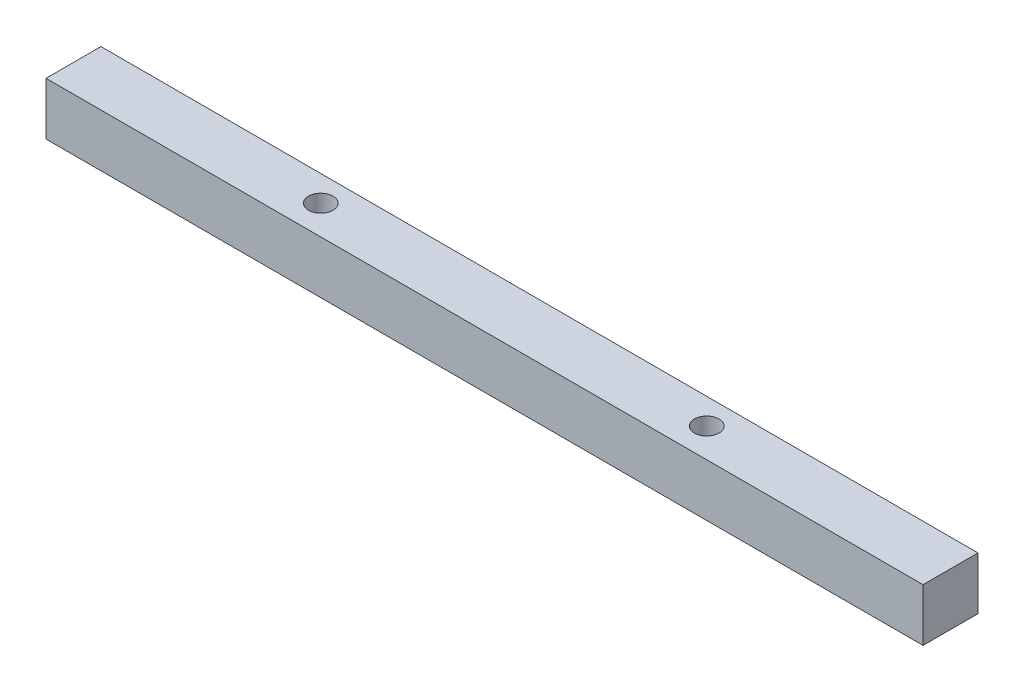
SolidWorks part; units mm, degrees
ref_plane "Front Plane" through (0, 0, 0) normal (0, 0, 1) x (1, 0, 0)
ref_plane "Top Plane" through (0, 0, 0) normal (0, 1, 0) x (1, 0, 0)
ref_plane "Right Plane" through (0, 0, 0) normal (1, 0, 0) x (0, 0, -1)
sketch "Sketch1" plane through (0, 0, 0) normal (1, 0, 0) x (0, 0, -1)
  line L1 (0, 0) -> (9.4, 0)
  line L2 (0, 0) -> (0, 9)
  line L3 (0, 9) -> (9.4, 9)
  line L4 (9.4, 0) -> (9.4, 9)
  dimension "D1" = 9.4
  dimension "D2" = 9
extrude "Boss-Extrude1" add sketch "Sketch1" along normal blind 150
sketch "Sketch2" plane through (0, 9, 0) normal (0, 1, 0) x (1, 0, 0)
  line L0 (75, 9.4) -> (75, 0) construction
  line L1 (150, 9.4) -> (0, 9.4) construction
  line L2 (150, 0) -> (0, 0) construction
  circle A0 centre (108, 4.9985) radius 2.1
  circle A1 centre (42, 4.9985) radius 2.1
  point P6 (75, 0)
  dimension "D1" = 4.2
  dimension "D2" = 33
extrude "Cut-Extrude1" cut sketch "Sketch2" against normal through all both and the other way through all contours A0 | A1
